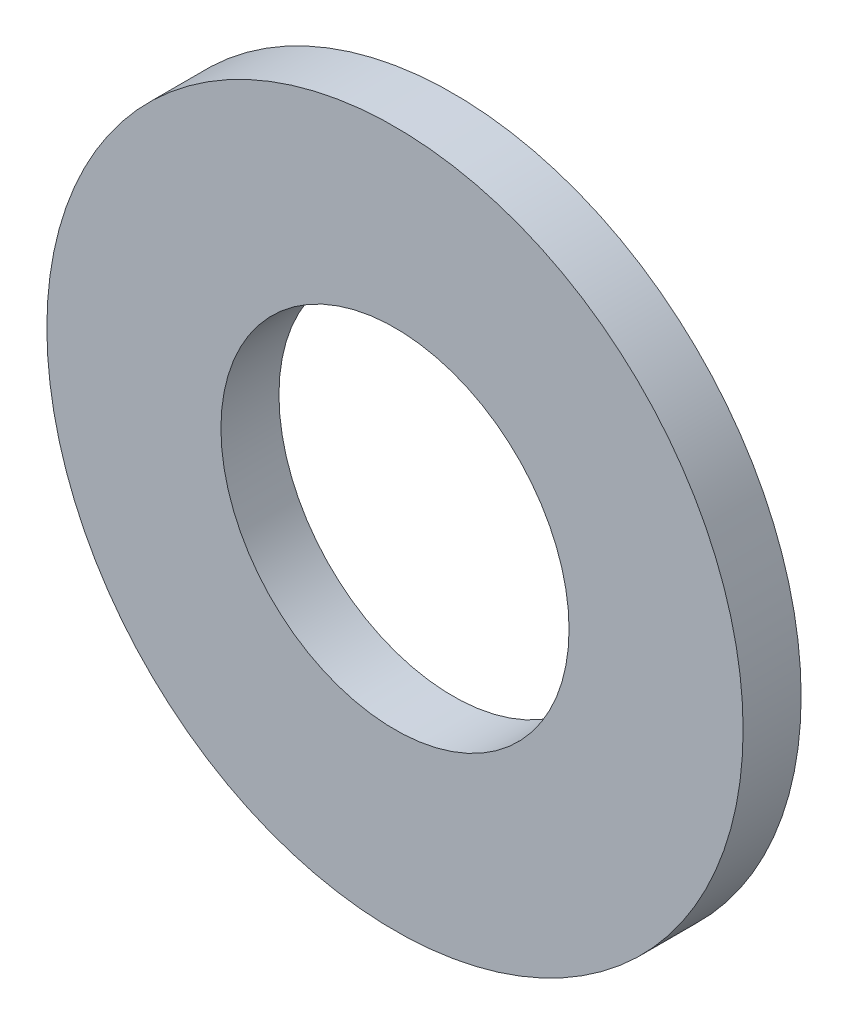
SolidWorks part; units mm, degrees
ref_plane "Plan de face" through (0, 0, 0) normal (0, 0, 1) x (1, 0, 0)
ref_plane "Plan de dessus" through (0, 0, 0) normal (0, 1, 0) x (1, 0, 0)
ref_plane "Plan de droite" through (0, 0, 0) normal (1, 0, 0) x (0, 0, -1)
sketch "Esquisse1" plane through (0, 0, 0) normal (0, 0, 1) x (1, 0, 0)
  circle A0 centre (0, 0) radius 3
  circle A1 centre (0, 0) radius 1.5
  dimension "D1" = 6
  dimension "D2" = 3
extrude "Boss.-Extru.1" add sketch "Esquisse1" along normal blind 0.5
